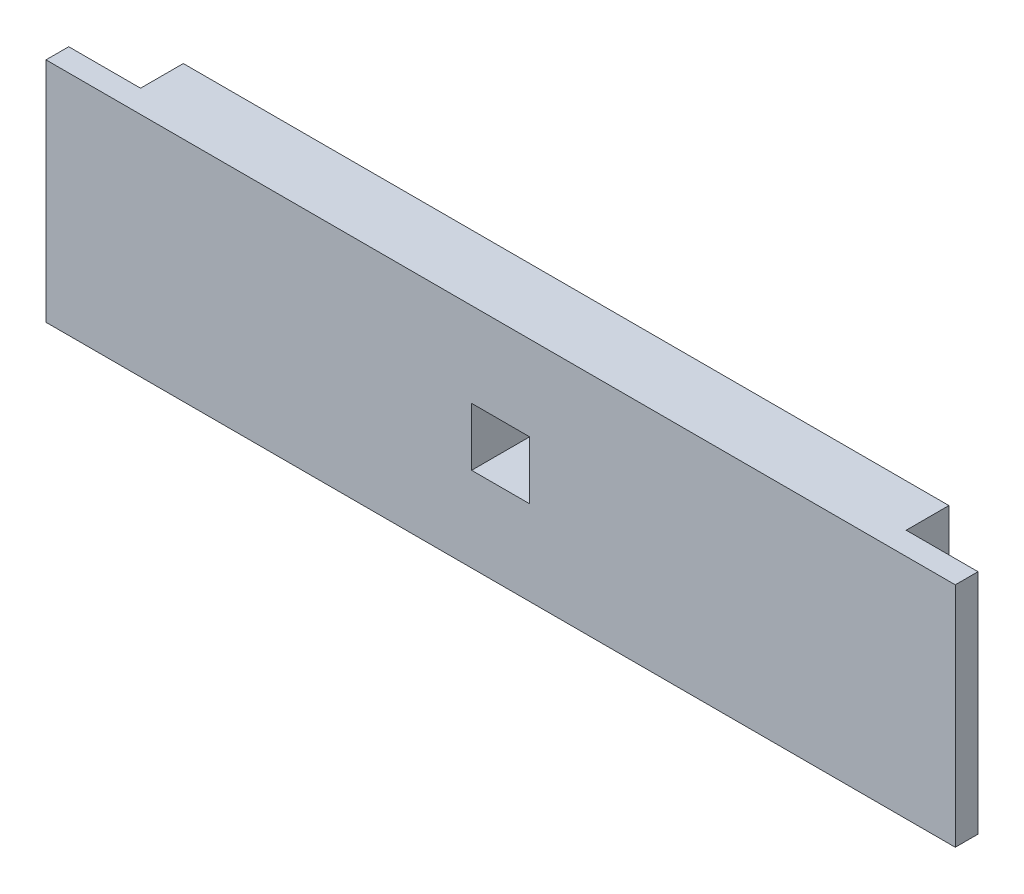
SolidWorks part; units mm, degrees
ref_plane "Front Plane" through (0, 0, 0) normal (0, 0, 1) x (1, 0, 0)
ref_plane "Top Plane" through (0, 0, 0) normal (0, 1, 0) x (1, 0, 0)
ref_plane "Right Plane" through (0, 0, 0) normal (1, 0, 0) x (0, 0, -1)
sketch "Sketch1" plane through (0, 0, 0) normal (0, 0, 1) x (1, 0, 0)
  line L1 (0, 0) -> (254, 0)
  line L2 (0, 0) -> (0, 63.5)
  line L3 (0, 63.5) -> (254, 63.5)
  line L4 (254, 0) -> (254, 63.5)
  dimension "D1" = 63.5
  dimension "D2" = 254
extrude "Boss-Extrude1" add sketch "Sketch1" along normal blind 18.288
sketch "Sketch2" plane through (0, 0, 18.288) normal (0, 0, 1) x (1, 0, 0)
  line L0 (127, 63.5) -> (127, 0) construction
  line L1 (254, 63.5) -> (0, 63.5) construction
  line L2 (0, 0) -> (254, 0) construction
  line L3 (0, 31.75) -> (254, 31.75) construction
  line L4 (0, 63.5) -> (0, 0) construction
  line L5 (254, 0) -> (254, 63.5) construction
  line L7 (118.8974, 23.6474) -> (135.1026, 23.6474)
  line L8 (118.8974, 23.6474) -> (118.8974, 39.8526)
  line L9 (118.8974, 39.8526) -> (135.1026, 39.8526)
  line L10 (135.1026, 23.6474) -> (135.1026, 39.8526)
  line L11 (127, 39.8526) -> (127, 23.6474) construction
  line L12 (118.8974, 31.75) -> (135.1026, 31.75) construction
  point P12 (127, 31.75)
  dimension "D1" = 16.2052
extrude "Cut-Extrude1" cut sketch "Sketch2" against normal through all
sketch "Sketch3" plane through (0, 0, 0) normal (0, 0, -1) x (-1, 0, 0)
  line L0 (-127, 63.5) -> (-127, 0) construction
  line L1 (-254, 63.5) -> (0, 63.5) construction
  line L2 (0, 0) -> (-254, 0) construction
  line L3 (-233.934, 63.5) -> (-233.934, 0)
  line L4 (-254, 0) -> (-254, 63.5) construction
  line L5 (-233.934, 63.5) -> (-254, 63.5)
  line L6 (-254, 63.5) -> (-254, 0)
  line L7 (-254, 0) -> (-233.934, 0)
  line L8 (0, 0) -> (-20.066, 0)
  line L9 (0, 63.5) -> (0, 0)
  line L10 (-20.066, 63.5) -> (0, 63.5)
  line L11 (-20.066, 63.5) -> (-20.066, 0)
  dimension "D1" = 20.066
extrude "Cut-Extrude2" cut sketch "Sketch3" against normal offset from surface (11.938 mm away) 6.35 up to face at (127, 31.75, 18.288)
